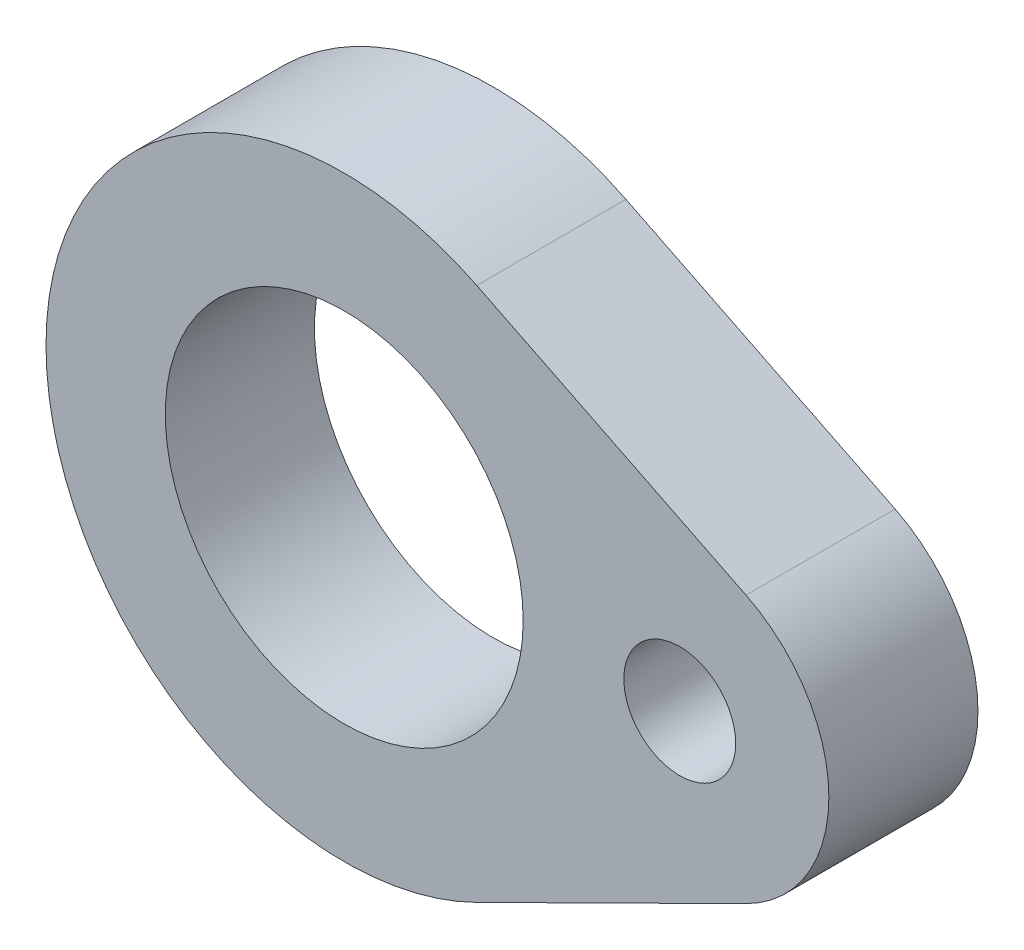
SolidWorks part; units mm, degrees
ref_plane "Front Plane" through (0, 0, 0) normal (0, 0, 1) x (1, 0, 0)
ref_plane "Top Plane" through (0, 0, 0) normal (0, 1, 0) x (1, 0, 0)
ref_plane "Right Plane" through (0, 0, 0) normal (1, 0, 0) x (0, 0, -1)
sketch "Sketch1" plane through (0, 0, 0) normal (0, 0, 1) x (1, 0, 0)
  line L1 (1.7778, 3.5832) -> (5.3889, 1.7916)
  line L2 (55, 0) -> (-55, 0) construction
  line L3 (5.3889, -1.7916) -> (1.7778, -3.5832)
  circle A0 centre (0, 0) radius 2.4
  arc A1 (1.7778, 3.5832) -> (1.7778, -3.5832) centre (0, 0) ccw
  arc A2 (5.3889, 1.7916) -> (5.3889, -1.7916) centre (4.5, 0) cw
  circle A3 centre (4.5, 0) radius 0.75
  point P11 (9, 0)
  dimension "D1" = 4.8
  dimension "D2" = 2
  dimension "D3" = 4
  dimension "D4" = 1.5
  dimension "D5" = 4.5
extrude "Boss-Extrude1" add sketch "Sketch1" along normal mid plane 2
